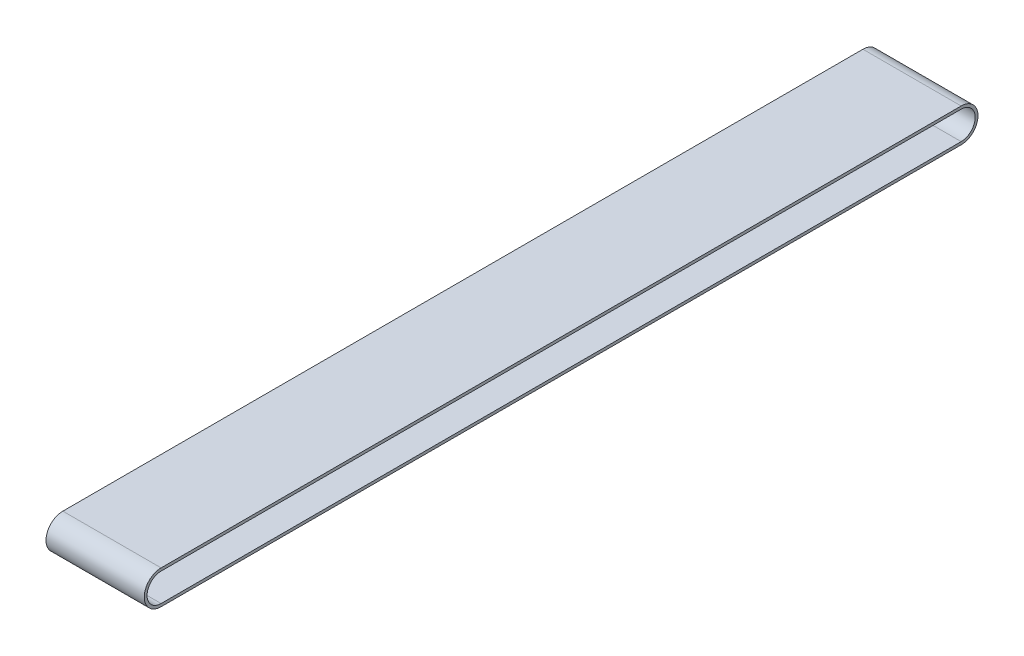
SolidWorks part; units mm, degrees
material "Caoutchouc silicone"
ref_plane "Plan de face" through (0, 0, 0) normal (0, 0, 1) x (1, 0, 0)
ref_plane "Plan de dessus" through (0, 0, 0) normal (0, 1, 0) x (1, 0, 0)
ref_plane "Plan de droite" through (0, 0, 0) normal (1, 0, 0) x (0, 0, -1)
sketch "Esquisse1" plane through (0, 0, 0) normal (1, 0, 0) x (0, 0, -1)
  line L0 (0, 0) -> (2850, 0) construction
  line L1 (0, 60) -> (2850, 60)
  line L2 (2850, -60) -> (0, -60)
  line L3 (0, 0) -> (6230, 0) construction
  line L4 (0, 50) -> (2850, 50)
  line L5 (2850, -50) -> (0, -50)
  arc A0 (0, 60) -> (0, -60) centre (0, 0) ccw
  arc A1 (2850, -60) -> (2850, 60) centre (2850, 0) ccw
  arc A2 (0, 50) -> (0, -50) centre (0, 0) ccw
  arc A3 (2850, 50) -> (2850, -50) centre (2850, 0) cw
  dimension "D1" = 120
  dimension "D2" = 120
  dimension "D6" = 100
  dimension "D3" = 2850
extrude "Boss.-Extru.1" add sketch "Esquisse1" along normal blind 350
